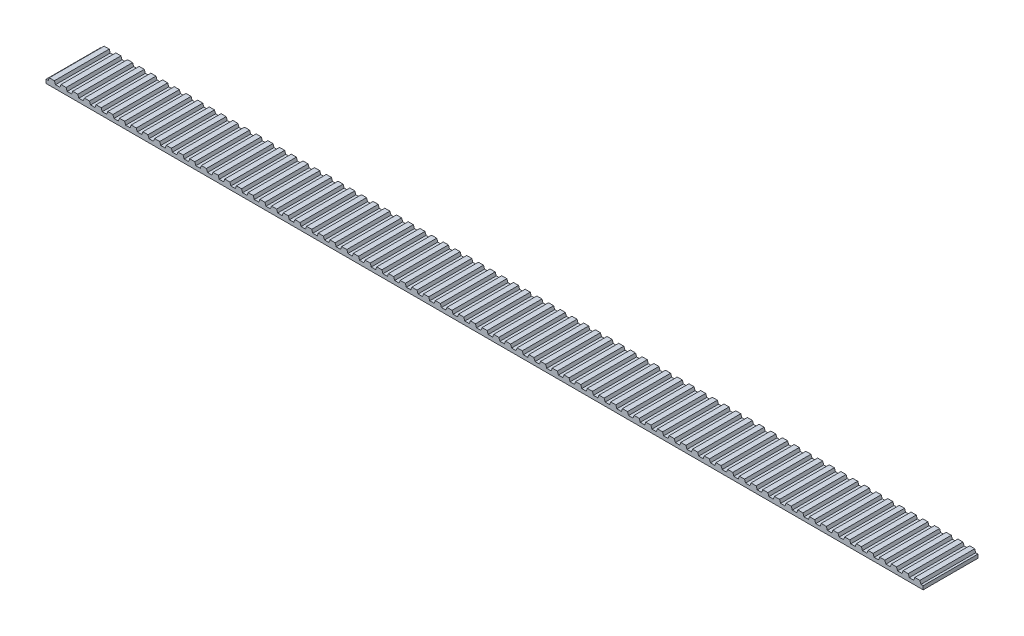
SolidWorks part; units mm, degrees
ref_plane "Front Plane" through (0, 0, 0) normal (0, 0, 1) x (1, 0, 0)
ref_plane "Top Plane" through (0, 0, 0) normal (0, 1, 0) x (1, 0, 0)
ref_plane "Right Plane" through (0, 0, 0) normal (1, 0, 0) x (0, 0, -1)
sketch "Sketch1" plane through (0, 0, 0) normal (0, 0, 1) x (1, 0, 0)
  line L0 (0, 0.635) -> (0.3866, 0.635) construction
  line L1 (0, 1.143) -> (152.4, 1.143)
  line L2 (0, 1.143) -> (0, 0)
  line L3 (0, 0) -> (152.4, 0)
  line L4 (152.4, 1.143) -> (152.4, 0)
  line L5 (0.3866, 0.635) -> (0.5715, 1.143) construction
  line L6 (1.3447, 1.143) -> (1.5296, 0.635) construction
  line L7 (1.5296, 0.635) -> (1.9162, 0.635) construction
  line L8 (0.3866, 0.635) -> (1.5296, 0.635) construction
  line L9 (0.9581, 0.635) -> (0.9581, 0) construction
  line L10 (2.9901, 1.143) -> (2.9901, 0) construction
  line L11 (5.0221, 1.143) -> (5.0221, 0) construction
  dimension "hs" = 1.143
  dimension "angle" = 40
  dimension "Pitch" = 2.032
  dimension "ht" = 0.508
  dimension "bt" = 1.143
  dimension "D1" = 0.7732
  dimension "D2" = 0.3866
  dimension "D3" = 152.4
  dimension "D4" = 2.032
extrude "Boss-Extrude1" add sketch "Sketch1" along normal mid plane 9.525
sketch "Sketch2" plane through (0, 0, 0) normal (0, 0, 1) x (1, 0, 0)
  line L0 (-0.5715, 1.143) -> (-0.3866, 0.635)
  line L1 (-0.3866, 0.635) -> (0.3866, 0.635)
  line L2 (0.3866, 0.635) -> (0.5715, 1.143)
  line L3 (0.5715, 1.143) -> (-0.5715, 1.143)
  line L4 (0.5715, 1.143) -> (1.3447, 1.143) construction
extrude "Cut-Extrude1" cut sketch "Sketch2" against normal through all and the other way through all
pattern_linear "LPattern1" count 76 spacing 2.032 along (1, 0, 0) of "Cut-Extrude1"
equation "\"D2@Sketch1\" = \"D1@Sketch1\"/2"
equation "\"D1@LPattern1\" =(\"D3@Sketch1\"/\"Pitch@Sketch1\")+1"
equation "\"D4@Sketch1\" = \"Pitch@Sketch1\""
equation "\"D3@LPattern1\" = \"Pitch@Sketch1\""
